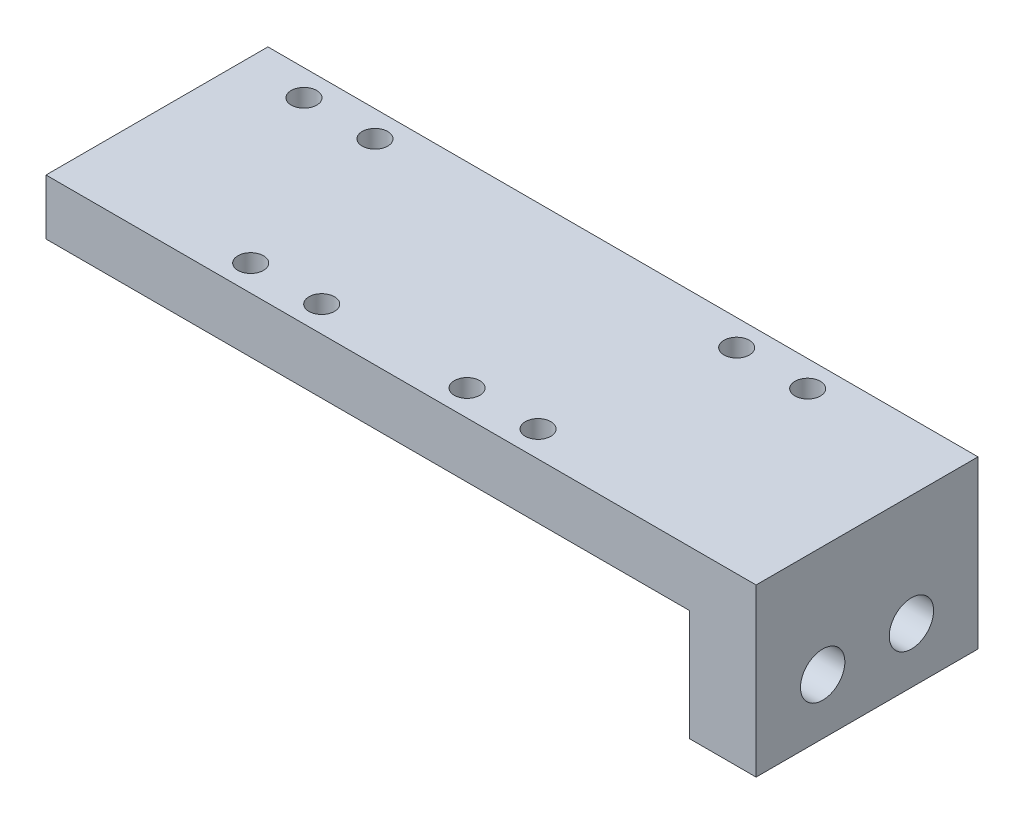
SolidWorks part; units mm, degrees
material "6063-T6"
ref_plane "Plano frontal" through (0, 0, 0) normal (0, 0, 1) x (1, 0, 0)
ref_plane "Plano superior" through (0, 0, 0) normal (0, 1, 0) x (1, 0, 0)
ref_plane "Plano direito" through (0, 0, 0) normal (1, 0, 0) x (0, 0, -1)
sketch "Esboço1" plane through (0, 0, 0) normal (0, 0, 1) x (1, 0, 0)
  line L0 (0, 0) -> (0, 10)
  line L1 (0, 10) -> (-58, 10)
  line L2 (-58, 10) -> (-58, 15)
  line L3 (-58, 15) -> (6, 15)
  line L4 (6, 15) -> (6, 0)
  line L5 (6, 0) -> (0, 0)
  dimension "D1" = 15
  dimension "D2" = 6
  dimension "D3" = 58
  dimension "D4" = 10
extrude "Ressalto-extrusão1" add sketch "Esboço1" along normal mid plane 20
sketch "Esboço2" plane through (0, 0, 0) normal (-1, 0, 0) x (0, 0, 1)
  line L0 (-4, 5) -> (4, 5) construction
  circle A0 centre (-4, 5) radius 2
  circle A1 centre (4, 5) radius 2
  point P4 (0, 5)
  dimension "D1" = 4
  dimension "D2" = 4
  dimension "D3" = 5
extrude "Corte-extrusão1" cut sketch "Esboço2" against normal blind 8
sketch "Esboço3" plane through (0, 15, 0) normal (0, 1, 0) x (1, 0, 0)
  line L3 (6, 70) -> (6, -70) construction
  line L5 (6, -10) -> (6, 10) construction
  circle A0 centre (-16, -7.65) radius 1.15
  circle A1 centre (-22.4, -7.65) radius 1.15
  circle A2 centre (-35.5, -7.65) radius 1.15
  circle A3 centre (-41.9, -7.65) radius 1.15
  circle A4 centre (-46, 7.65) radius 1.15
  circle A5 centre (-52.4, 7.65) radius 1.15
  circle A6 centre (-13.4, 7.65) radius 1.15
  circle A7 centre (-7, 7.65) radius 1.15
  dimension "D1" = 41.5
  dimension "D2" = 6.4
  dimension "D3" = 6.4
  dimension "D4" = 6.4
  dimension "D5" = 6.4
  dimension "D6" = 22
  dimension "D7" = 13
  dimension "D8" = 52
extrude "Corte-extrusão2" cut sketch "Esboço3" against normal through all both and the other way through all
